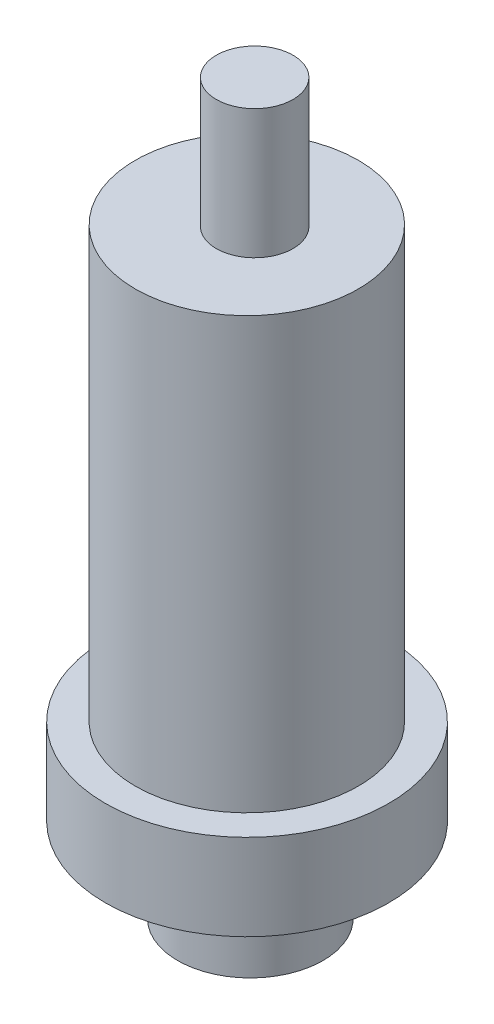
SolidWorks part; units mm, degrees
ref_plane "Front Plane" through (0, 0, 0) normal (0, 0, 1) x (1, 0, 0)
ref_plane "Top Plane" through (0, 0, 0) normal (0, 1, 0) x (1, 0, 0)
ref_plane "Right Plane" through (0, 0, 0) normal (1, 0, 0) x (0, 0, -1)
sketch "Sketch1" plane through (0, 0, 0) normal (0, 1, 0) x (1, 0, 0)
  circle A0 centre (0, 1.8009) radius 16.4579
extrude "Boss-Extrude1" add sketch "Sketch1" along normal blind 10
sketch "Sketch2" plane through (0, 10, 0) normal (0, 1, 0) x (1, 0, 0)
  circle A0 centre (0, 1.7734) radius 12.9535
extrude "Boss-Extrude2" add sketch "Sketch2" along normal blind 50
sketch "Sketch3" plane through (0, 0, 0) normal (0, -1, 0) x (-1, 0, 0)
  circle A0 centre (0, 2.1789) radius 8.4463
extrude "Boss-Extrude3" add sketch "Sketch3" along normal blind 10
sketch "Sketch4" plane through (0, 60, 0) normal (0, 1, 0) x (1, 0, 0)
  circle A0 centre (0.6429, 2.0418) radius 4.4563
extrude "Boss-Extrude4" add sketch "Sketch4" along normal blind 15
